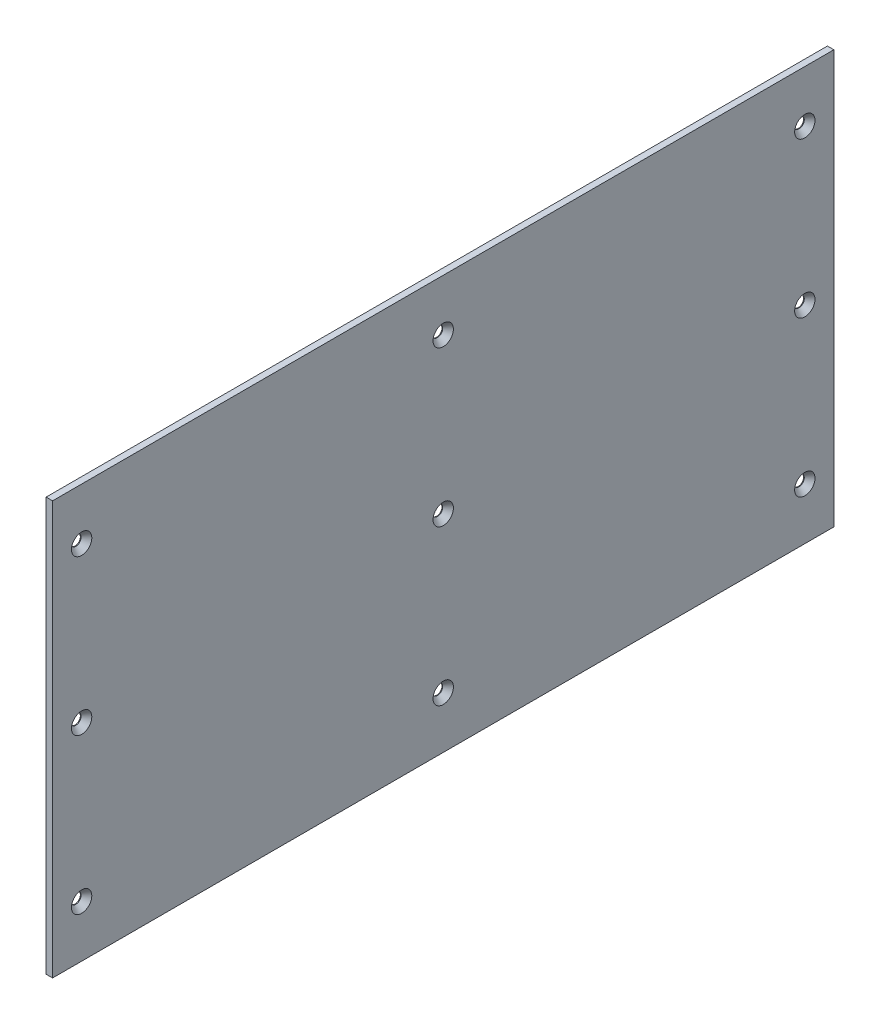
SolidWorks part; units mm, degrees
material "2024-T4"
ref_plane "Front Plane" through (0, 0, 0) normal (0, 0, 1) x (1, 0, 0)
ref_plane "Top Plane" through (0, 0, 0) normal (0, 1, 0) x (1, 0, 0)
ref_plane "Right Plane" through (0, 0, 0) normal (1, 0, 0) x (0, 0, -1)
sketch "Sketch1" plane through (0, 0, 0) normal (1, 0, 0) x (0, 0, -1)
  line L1 (-187.6281, -128.5307) -> (196.5469, -128.5307)
  line L2 (-187.6281, -128.5307) -> (-187.6281, 74.6693)
  line L3 (-187.6281, 74.6693) -> (196.5469, 74.6693)
  line L4 (196.5469, -128.5307) -> (196.5469, 74.6693)
  dimension "D1" = 384.175
  dimension "D2" = 203.2
extrude "Boss-Extrude1" add sketch "Sketch1" along normal blind 3.175
sketch "Sketch3" plane through (3.175, 0, 0) normal (1, 0, 0) x (0, 0, -1)
  line L0 (4.4594, -128.5307) -> (4.4594, 74.6693)
  line L3 (-187.6281, -128.5307) -> (196.5469, -128.5307) construction
  line L4 (196.5469, 74.6693) -> (-187.6281, 74.6693) construction
  circle A0 centre (-173.3406, 49.2693) radius 2.5527
  circle A1 centre (-173.3406, -26.9307) radius 2.5527
  circle A2 centre (-173.3406, -103.1307) radius 2.5527
  circle A3 centre (4.4594, -103.1307) radius 2.5527
  circle A4 centre (182.2594, -103.1307) radius 2.5527
  circle A5 centre (182.2594, -26.9307) radius 2.5527
  circle A6 centre (182.2594, 49.2693) radius 2.5527
  circle A7 centre (4.4594, 49.2693) radius 2.5527
  circle A8 centre (4.4594, -26.9307) radius 2.5527
  dimension "D11" = 5.1054
  dimension "D7" = 5.1054
  dimension "D8" = 5.1054
  dimension "D9" = 5.1054
  dimension "D10" = 5.1054
  dimension "D12" = 5.1054
  dimension "D1" = 192.0875
  dimension "D2" = 192.0875
  dimension "D3" = 192.0875
  dimension "D4" = 177.8
  dimension "D5" = 177.8
  dimension "D6" = 177.8
  dimension "D13" = 25.4
  dimension "D14" = 76.2
  dimension "D15" = 76.2
hole_wizard "CSK for #10 Flat Head Machine Screw1" positions "Sketch7" profile "Sketch6" countersink size "#10" standard "ANSI Inch" end condition through all
sketch "Sketch7" plane through (3.175, 0, 0) normal (1, 0, 0) x (0, 0, -1)
  point P0 (-173.3406, 49.2693)
  point P3 (-173.3406, -26.9307)
  point P6 (-173.3406, -103.1307)
  point P9 (4.4594, 49.2693)
  point P12 (4.4594, -26.9307)
  point P15 (4.4594, -103.1307)
  point P18 (182.2594, -26.9307)
  point P21 (182.2594, -103.1307)
sketch "Sketch6" plane through (3.175, 49.2693, 173.3406) normal (0, 1, 0) x (0, 0, -1)
  line L0 (0, 0) -> (0, 3.175)
  line L1 (0, 3.175) -> (2.5527, 3.175)
  line L2 (2.5527, 3.175) -> (2.5527, 2.8152)
  line L3 (2.5527, 2.8152) -> (4.9999, 0)
  line L5 (4.9999, 0) -> (0, 0)
  line L6 (-2.5527, 2.8152) -> (-4.9999, 0) construction
  line L11 (0, -6.35) -> (0, 107.95) construction
  dimension "Thru Hole Dia." = 5.1054
  dimension "Thru Hole Depth" = 3.175
  dimension "Near C'Sink Dia." = 9.9998
  dimension "Near C'Sink Angle" = 82
hole_wizard "CSK for #10 Flat Head Machine Screw2" positions "Sketch9" profile "Sketch8" countersink size "#10" standard "ANSI Inch" end condition through all
sketch "Sketch9" plane through (3.175, 0, 0) normal (1, 0, 0) x (0, 0, -1)
  point P0 (182.2594, 49.2693)
sketch "Sketch8" plane through (3.175, 49.2693, -182.2594) normal (0, 1, 0) x (0, 0, -1)
  line L0 (0, 0) -> (0, 3.175)
  line L1 (0, 3.175) -> (2.5527, 3.175)
  line L2 (2.5527, 3.175) -> (2.5527, 2.8152)
  line L3 (2.5527, 2.8152) -> (4.9999, 0)
  line L5 (4.9999, 0) -> (0, 0)
  line L6 (-2.5527, 2.8152) -> (-4.9999, 0) construction
  line L11 (0, -6.35) -> (0, 107.95) construction
  dimension "Thru Hole Dia." = 5.1054
  dimension "Thru Hole Depth" = 3.175
  dimension "Near C'Sink Dia." = 9.9998
  dimension "Near C'Sink Angle" = 82
